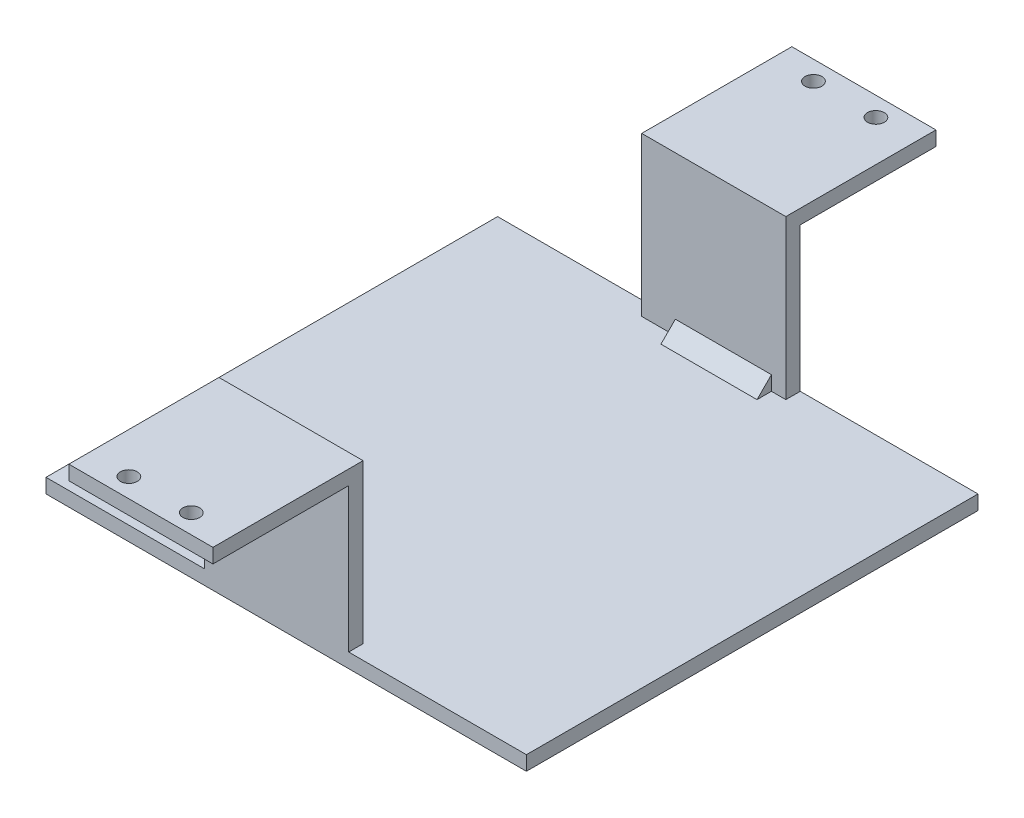
SolidWorks part; units mm, degrees
ref_plane "Front Plane" through (0, 0, 0) normal (0, 0, 1) x (1, 0, 0)
ref_plane "Top Plane" through (0, 0, 0) normal (0, 1, 0) x (1, 0, 0)
ref_plane "Right Plane" through (0, 0, 0) normal (1, 0, 0) x (0, 0, -1)
sketch "Sketch1" plane through (0, 0, 0) normal (0, 1, 0) x (1, 0, 0)
  line L1 (-50, 47) -> (50, 47)
  line L2 (-50, 47) -> (-50, -47)
  line L3 (-50, -47) -> (50, -47)
  line L4 (50, 47) -> (50, -47)
  point P4 (0, 47)
  point P6 (-50, 0)
  dimension "D1" = 100
  dimension "D2" = 94
extrude "Boss-Extrude1" add sketch "Sketch1" against normal blind 3
sketch "Sketch2" plane through (0, 0, 0) normal (0, 1, 0) x (1, 0, 0)
  line L0 (50, 47) -> (-50, 47) construction
  line L1 (13, 47) -> (-17, 47)
  line L2 (13, 47) -> (13, 44)
  line L3 (13, 44) -> (-17, 44)
  line L4 (-17, 47) -> (-17, 44)
  line L5 (-50, -47) -> (50, -47) construction
  line L6 (13, -47) -> (-17, -47)
  line L7 (13, -47) -> (13, -44)
  line L8 (13, -44) -> (-17, -44)
  line L9 (-17, -47) -> (-17, -44)
  line L10 (50, -47) -> (50, 47) construction
  point P14 (0, 0)
  dimension "D1" = 3
  dimension "D2" = 3
  dimension "D3" = 37
  dimension "D4" = 30
extrude "Boss-Extrude2" add sketch "Sketch2" along normal blind 33
sketch "Sketch3" plane through (0, 0, 0) normal (1, 0, 0) x (0, 0, -1)
  line L0 (-44, 3) -> (-41, 0)
  line L1 (-44, 33) -> (-44, 0) construction
  line L2 (-47, 0) -> (47, 0) construction
  line L3 (-41, 0) -> (-44, 0)
  line L4 (-44, 0) -> (-44, 3)
  line L5 (44, 3) -> (41, 0)
  line L6 (44, 33) -> (44, 0) construction
  line L7 (41, 0) -> (44, 0)
  line L8 (44, 0) -> (44, 3)
  line L9 (-47, 30) -> (-50, 30)
  line L10 (-50, 30) -> (-47, 27)
  line L11 (-47, 33) -> (-47, 0) construction
  line L12 (-47, 27) -> (-47, 30)
  line L13 (47, 30) -> (47, 27)
  line L14 (47, 33) -> (47, 0) construction
  line L15 (47, 30) -> (50, 30)
  line L16 (47, 27) -> (50, 30)
  line L17 (-47, 33) -> (-44, 33) construction
  dimension "D1" = 3
  dimension "D2" = 3
extrude "Boss-Extrude3" add sketch "Sketch3" along normal mid plane 20
sketch "Sketch4" plane through (0, 33, 0) normal (0, 1, 0) x (1, 0, 0)
  line L0 (-17, -44) -> (-17, -47) construction
  line L1 (-17, 47) -> (13, 47)
  line L2 (-17, 47) -> (-17, 75.25)
  line L3 (-17, 75.25) -> (13, 75.25)
  line L4 (13, 47) -> (13, 75.25)
  line L5 (13, -47) -> (-17, -47)
  line L6 (13, -47) -> (13, -75.25)
  line L7 (13, -75.25) -> (-17, -75.25)
  line L8 (-17, -47) -> (-17, -75.25)
  line L9 (13, 44) -> (13, 47) construction
  circle A0 centre (-8.5, 71.25) radius 1.75
  circle A1 centre (4.5, 71.25) radius 1.75
  circle A2 centre (-8.5, -71.25) radius 1.75
  circle A3 centre (4.5, -71.25) radius 1.75
  point P22 (0, 0)
  point P23 (0, 0)
  point P24 (0, 0)
  point P25 (-2, -75.25)
  point P26 (0, 0)
  point P27 (0, 0)
  point P28 (0, 0)
  point P29 (0, 0)
  point P31 (0, 0)
  dimension "D1" = 3.5
  dimension "D3" = 6.5
  dimension "D4" = 4
  dimension "D5" = 4
  dimension "D6" = 71.25
  dimension "D2" = 6.5
extrude "Boss-Extrude4" add sketch "Sketch4" against normal blind 3
